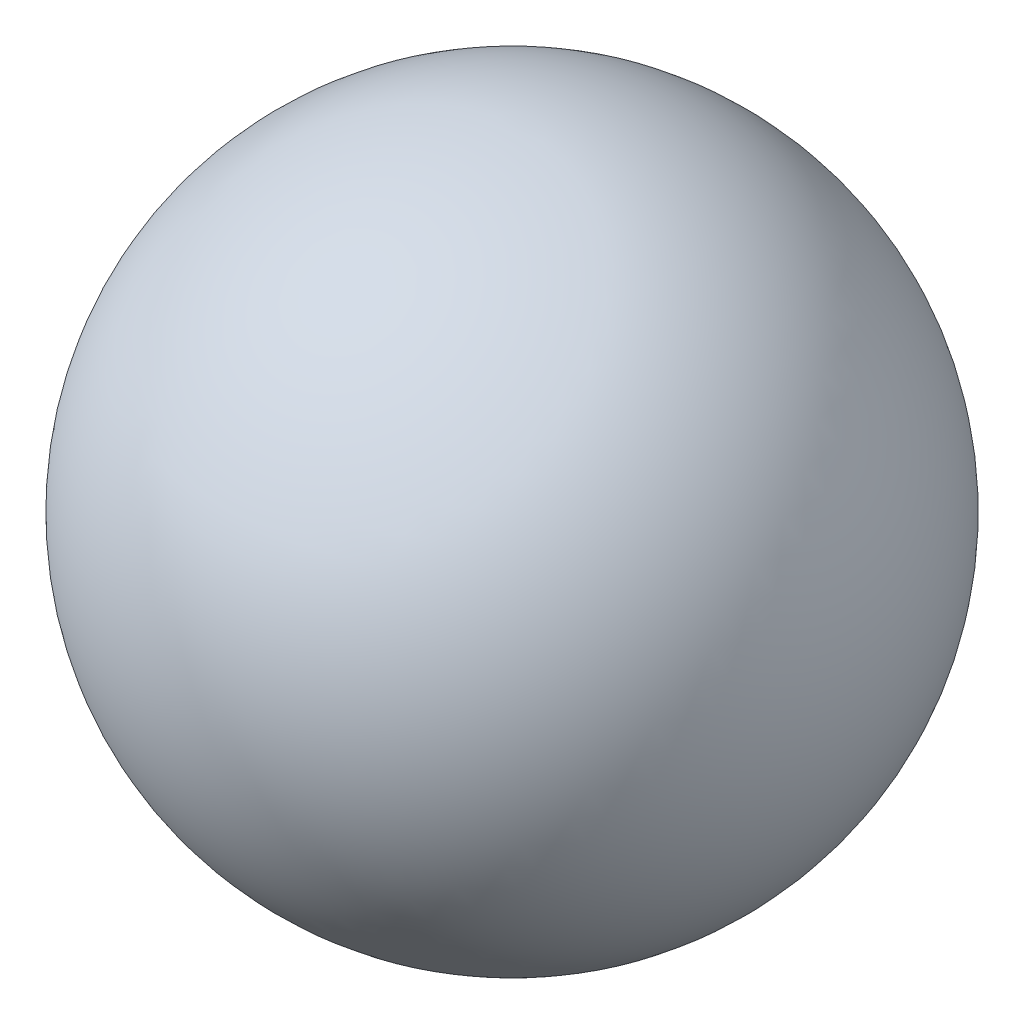
SolidWorks part; units mm, degrees
ref_plane "前视基准面" through (0, 0, 0) normal (0, 0, 1) x (1, 0, 0)
ref_plane "上视基准面" through (0, 0, 0) normal (0, 1, 0) x (1, 0, 0)
ref_plane "右视基准面" through (0, 0, 0) normal (1, 0, 0) x (0, 0, -1)
sketch "草图1" plane through (0, 0, 0) normal (0, 0, 1) x (1, 0, 0)
  line L0 (0, 8.5) -> (0, -8.5) construction
  line L1 (0, 8.5) -> (0, -8.5)
  arc A0 (0, -8.5) -> (0, 8.5) centre (0, 0) ccw
  dimension "D1" = 8.5
revolve "旋转1" add sketch "草图1" angle 360 about L0
